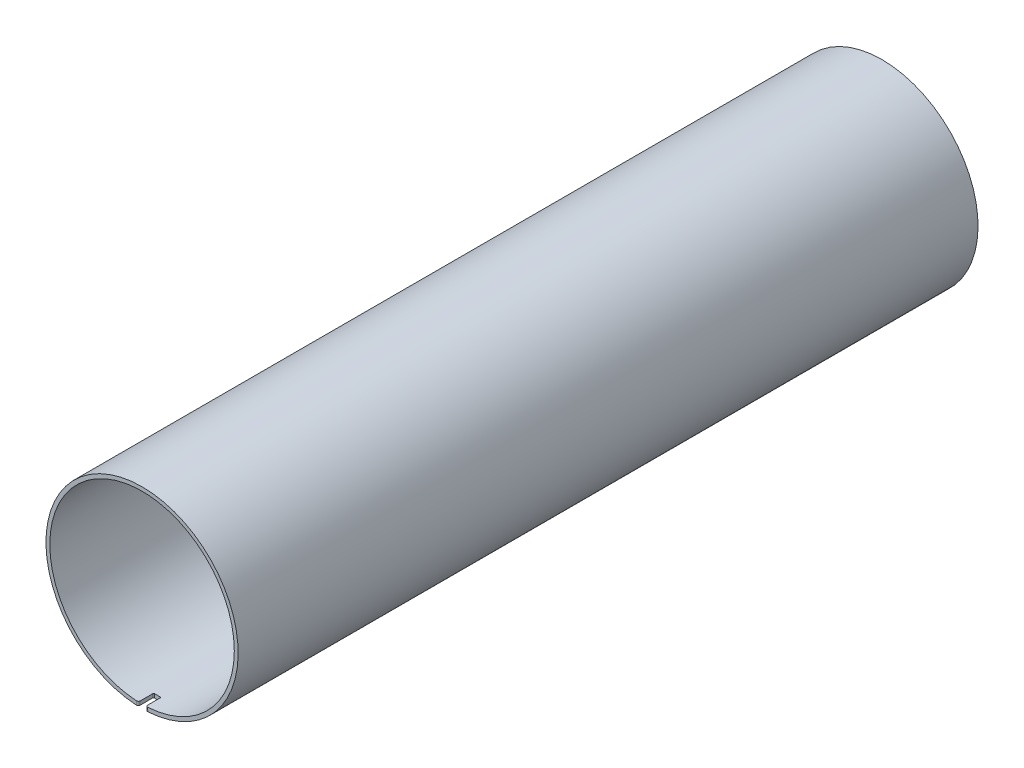
SolidWorks part; units mm, degrees
ref_plane "Спереди" through (0, 0, 0) normal (0, 0, 1) x (1, 0, 0)
ref_plane "Сверху" through (0, 0, 0) normal (0, 1, 0) x (1, 0, 0)
ref_plane "Справа" through (0, 0, 0) normal (1, 0, 0) x (0, 0, -1)
sketch "Эскиз1" plane through (0, 0, 0) normal (0, 0, 1) x (1, 0, 0)
  circle A0 centre (0, 0) radius 50
  circle A1 centre (0, 0) radius 48
  dimension "D1" = 100
  dimension "D2" = 2
extrude "Бобышка-Вытянуть1" add sketch "Эскиз1" along normal blind 385
sketch "Эскиз3" plane through (0, 0, 385) normal (0, 0, 1) x (1, 0, 0)
  line L0 (0, 0) -> (0, -53.3234) construction
  line L1 (-1.92, -47.9616) -> (-2, -49.96)
  line L2 (1.92, -47.9616) -> (2, -49.96)
  circle A0 centre (0, 0) radius 50 construction
  circle A1 centre (0, 0) radius 48 construction
  arc A2 (-2, -49.96) -> (2, -49.96) centre (0, 0) ccw
  arc A3 (-1.92, -47.9616) -> (1.92, -47.9616) centre (0, 0) ccw
  dimension "D1" = 4
extrude "Вырез-Вытянуть1" cut sketch "Эскиз3" against normal blind 8
ref_plane "Плоскость1" through (0, 0, 192.5) normal (0, 0, 1) x (1, 0, 0)
mirror "Зеркальное отражение3" about plane through (0, 0, 192.5) normal (0, 0, 1) of "Вырез-Вытянуть1"
fillet "Скругление1" radius 0.5 4 edges at (1.96, -48.9608, 377) (-1.96, -48.9608, 377) (1.96, -48.9608, 8) (-1.96, -48.9608, 8)
fillet "Скругление2" radius 1 4 edges at (1.96, -48.9608, 385) (-1.96, -48.9608, 385) (-1.96, -48.9608, 0) (1.96, -48.9608, 0)
